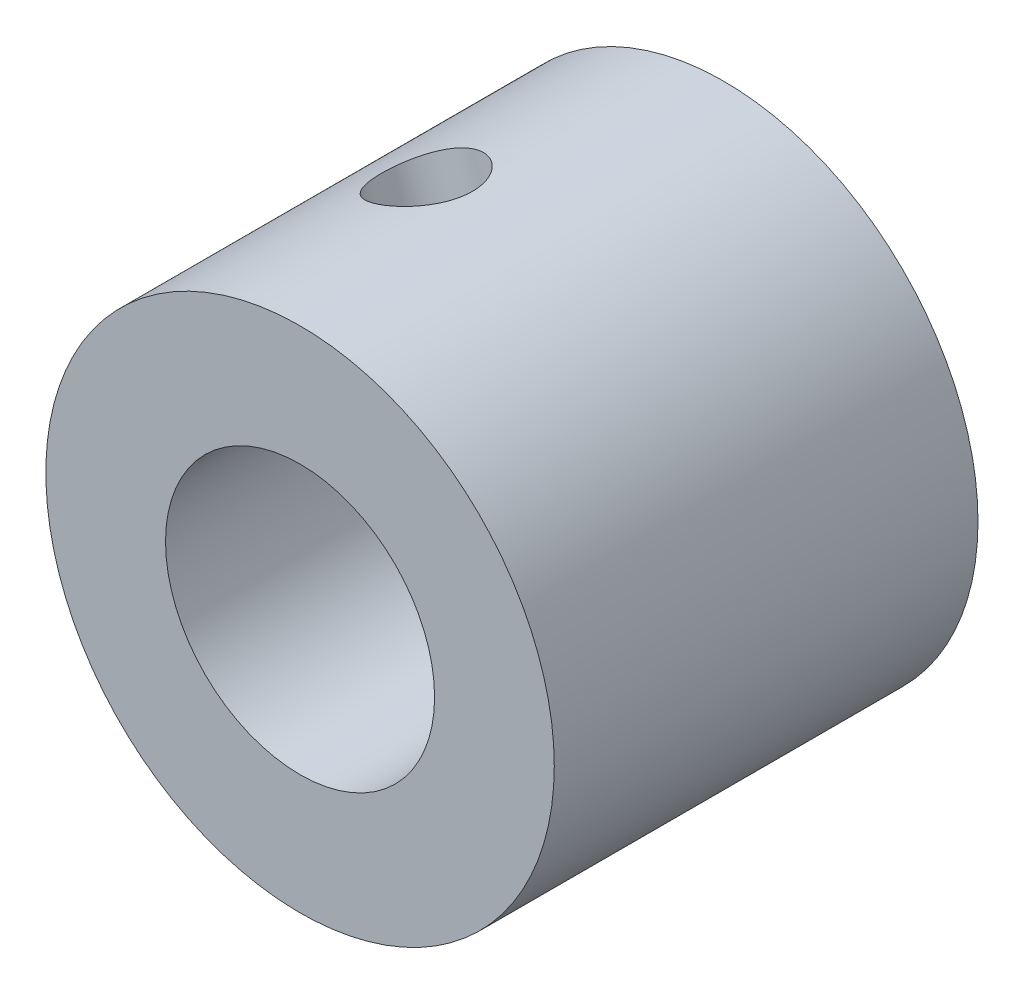
SolidWorks part; units mm, degrees
material "1060 Alloy"
ref_plane "Front Plane" through (0, 0, 0) normal (0, 0, 1) x (1, 0, 0)
ref_plane "Top Plane" through (0, 0, 0) normal (0, 1, 0) x (1, 0, 0)
ref_plane "Right Plane" through (0, 0, 0) normal (1, 0, 0) x (0, 0, -1)
sketch "Sketch1" plane through (0, 0, 0) normal (0, 0, 1) x (1, 0, 0)
  circle A0 centre (0, 0) radius 3.175
  circle A1 centre (0, 0) radius 6
  dimension "D1" = 6.35
  dimension "D2" = 12
extrude "Boss-Extrude1" add sketch "Sketch1" along normal blind 10
hole_wizard "#4-40 Tapped Hole1" positions "3DSketch1" profile "Sketch4" tap size "#4-40" standard "ANSI Inch"
sketch3d "3DSketch1"
  point P0 (-1.8688, 5.7016, 5.17)
sketch "Sketch4" plane through (-1.8688, 5.7016, 5.17) normal (0, 0, 1) x (-0.9503, -0.3115, 0)
  line L0 (0, 0) -> (0, 5.6792)
  line L1 (0, 5.6792) -> (1.1303, 5)
  line L2 (1.1303, 5) -> (1.1303, 0)
  line L5 (1.1303, 0) -> (0, 0)
  line L10 (0, 5.6792) -> (-1.1303, 5) construction
  line L11 (0, -6.35) -> (0, 107.95) construction
  dimension "Tap Drill Dia." = 2.2606
  dimension "Tap Drill Depth" = 5
  dimension "Drill Angle" = 118
cosmetic thread "Hole Thread1" parameters "D1"=3.033, "D2"=1.524
